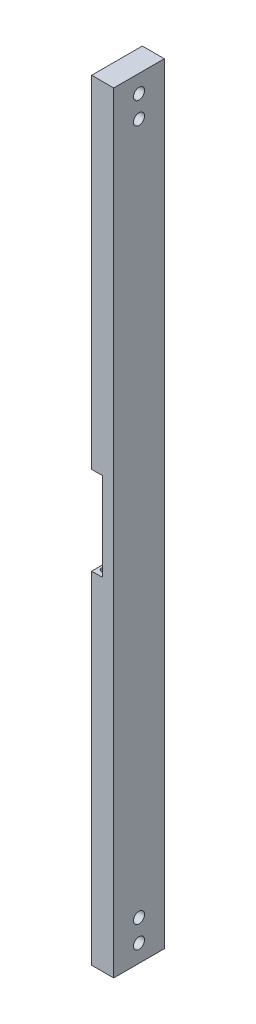
SolidWorks part; units mm, degrees
material "1060 Alloy"
ref_plane "Front Plane" through (0, 0, 0) normal (0, 0, 1) x (1, 0, 0)
ref_plane "Top Plane" through (0, 0, 0) normal (0, 1, 0) x (1, 0, 0)
ref_plane "Right Plane" through (0, 0, 0) normal (1, 0, 0) x (0, 0, -1)
sketch "Sketch2" plane through (0, 0, 0) normal (0, 1, 0) x (1, 0, 0)
  line L1 (-5, 11.5) -> (5, 11.5)
  line L2 (-5, 11.5) -> (-5, -11.5)
  line L3 (-5, -11.5) -> (5, -11.5)
  line L4 (5, 11.5) -> (5, -11.5)
  line L5 (-5, 11.5) -> (5, -11.5) construction
  line L6 (-5, -11.5) -> (5, 11.5) construction
  point P0 (0, 0)
  dimension "D1" = 10
  dimension "D2" = 23
extrude "Boss-Extrude1" add sketch "Sketch2" along normal mid plane 350
sketch "Sketch3" plane through (5, 0, 0) normal (1, 0, 0) x (0, 0, -1)
  line L0 (-11.5, 175) -> (11.5, 175) construction
  line L1 (-11.5, 175) -> (-11.5, -175) construction
  circle A0 centre (0, 167) radius 2.5
  circle A1 centre (0, 157) radius 2.5
  dimension "D1" = 5
  dimension "D2" = 5
  dimension "D3" = 8
  dimension "D4" = 10
  dimension "D5" = 11.5
  dimension "D6" = 11.5
extrude "Cut-Extrude1" cut sketch "Sketch3" against normal through all
sketch "Sketch4" plane through (5, 0, 0) normal (1, 0, 0) x (0, 0, -1)
  line L0 (-11.5, 175) -> (11.5, 175) construction
  line L1 (-11.5, 175) -> (-11.5, -175) construction
  circle A0 centre (0, 140) radius 2
  circle A1 centre (0, 116) radius 2
  dimension "D2" = 4
  dimension "D3" = 4
  dimension "D1" = 35
  dimension "D4" = 11.5
  dimension "D5" = 11.5
  dimension "D6" = 24
sketch "Sketch5" plane through (5, 0, 0) normal (1, 0, 0) x (0, 0, -1)
  line L0 (-11.5, -175) -> (11.5, -175) construction
  line L1 (-11.5, 175) -> (-11.5, -175) construction
  circle A0 centre (0, -167) radius 2.5
  circle A1 centre (0, -157) radius 2.5
  dimension "D1" = 5
  dimension "D2" = 5
  dimension "D3" = 10
  dimension "D4" = 8
  dimension "D5" = 11.5
extrude "Cut-Extrude2" cut sketch "Sketch5" against normal through all
sketch "Sketch6" plane through (0, 0, 11.5) normal (0, 0, 1) x (1, 0, 0)
  line L0 (-5, 175) -> (-5, -175) construction
  line L1 (-5, 20) -> (0, 20)
  line L2 (-5, 20) -> (-5, -20)
  line L3 (-5, -20) -> (0, -20)
  line L4 (0, 20) -> (0, -20)
  line L5 (-5, 20) -> (0, -20) construction
  line L6 (-5, -20) -> (0, 20) construction
  point P0 (-2.5, 0)
  point P7 (-5, 0)
  dimension "D1" = 5
  dimension "D2" = 40
extrude "Cut-Extrude3" cut sketch "Sketch6" against normal blind 7
sketch "Sketch7" plane through (0, 20, 0) normal (0, -1, 0) x (1, 0, 0)
  line L0 (0, 4.5) -> (-5, 4.5) construction
  line L1 (0, 4.5) -> (0, 11.5) construction
  line L2 (-5, 4.5) -> (-5, 11.5) construction
  line L3 (0, 11.5) -> (-5, 11.5) construction
  line L4 (0, 4.5) -> (-5, 4.5)
  line L5 (0, 4.5) -> (0, 11.5)
  line L6 (-5, 4.5) -> (-5, 11.5)
  line L7 (0, 11.5) -> (-5, 11.5)
  circle A0 centre (-2.5, 8) radius 1.5
  point P4 (-5, 8)
  dimension "D1" = 3
  dimension "D2" = 2.5
extrude "Cut-Extrude6" cut sketch "Sketch7" against normal blind 5 contours A0
ref_plane "Plane1" through (0, 0, 0) normal (0, -1, 0) x (-1, 0, 0)
mirror "Mirror1" about plane through (0, 0, 0) normal (0, -1, 0) of "Cut-Extrude6"
ref_plane "Plane2" through (0, 0, 0) normal (0, 0, 1) x (1, 0, 0)
mirror "Mirror2" about plane through (0, 0, 0) normal (0, 0, 1) of "Cut-Extrude3", "Cut-Extrude6", "Mirror1"
